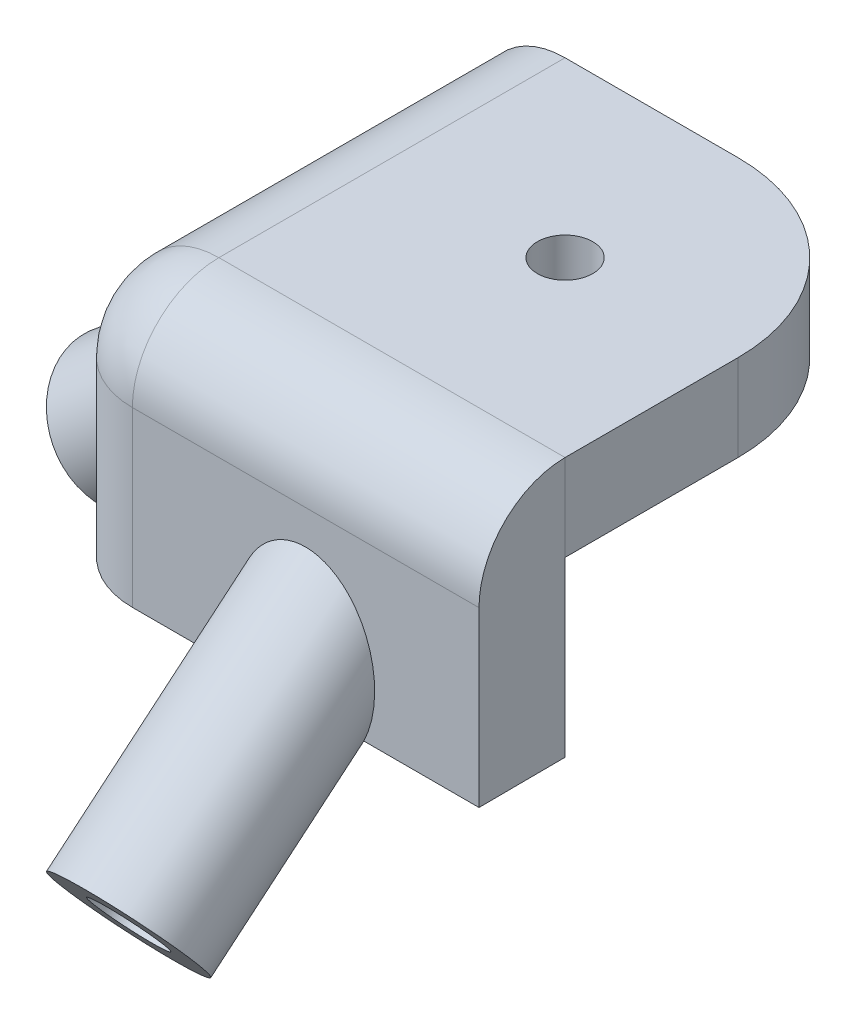
SolidWorks part; units mm, degrees
ref_plane "前基準面" through (0, 0, 0) normal (0, 0, 1) x (1, 0, 0)
ref_plane "上基準面" through (0, 0, 0) normal (0, 1, 0) x (1, 0, 0)
ref_plane "右基準面" through (0, 0, 0) normal (1, 0, 0) x (0, 0, -1)
sketch "草圖1" plane through (0, 0, 0) normal (0, 1, 0) x (1, 0, 0)
  line L1 (-10, -10) -> (10, -10)
  line L2 (-10, -10) -> (-10, 10)
  line L3 (-10, 10) -> (10, 10)
  line L4 (10, -10) -> (10, 10)
  line L5 (-10, -10) -> (10, 10) construction
  line L6 (-10, 10) -> (10, -10) construction
  point P0 (0, 0)
  dimension "D1" = 20
  dimension "D2" = 20
extrude "填料-伸長1" add sketch "草圖1" along normal blind 8
ref_plane "平面1" through (0, -1.6186, 1.929) normal (0, -0.6428, 0.766) x (1, 0, 0)
sketch "草圖2" plane through (0, -1.6186, 1.929) normal (0, -0.6428, 0.766) x (1, 0, 0)
  line L0 (-10, 6.4279) -> (10, 6.4279) construction
  line L1 (-10, 6.4279) -> (10, 6.4279) construction
  circle A0 centre (0, 6.4279) radius 4
  dimension "D1" = 8
extrude "填料-伸長2" add sketch "草圖2" along normal blind 25
ref_plane "平面2" through (-1.929, -1.6186, 0) normal (-0.766, -0.6428, 0) x (0, 0, 1)
sketch "草圖3" plane through (-1.929, -1.6186, 0) normal (-0.766, -0.6428, 0) x (0, 0, 1)
  line L0 (-10, 6.4279) -> (10, 6.4279) construction
  line L1 (-10, 6.4279) -> (10, 6.4279) construction
  circle A0 centre (0, 6.4279) radius 4
  dimension "D1" = 8
extrude "填料-伸長3" add sketch "草圖3" along normal blind 25
sketch "草圖4" plane through (0, 8, 0) normal (0, 1, 0) x (1, 0, 0)
  line L0 (0, 10) -> (10, 10)
  line L1 (10, 10) -> (10, 0)
  circle A0 centre (0, 0) radius 1.6
  arc A1 (10, 0) -> (0, 10) centre (0, 0) ccw
  dimension "D1" = 3.2
  dimension "D2" = 20
extrude "除料-伸長1" cut sketch "草圖4" against normal through all
sketch "草圖5" plane through (0, 0, 0) normal (0, -1, 0) x (1, 0, 0)
  line L0 (0, -10) -> (-10, -10) construction
  line L1 (10, 10) -> (10, 0) construction
  line L2 (0, -10) -> (-10, -10)
  line L3 (10, 10) -> (10, 0)
  line L4 (10, 10) -> (-10, 10)
  line L5 (-10, 10) -> (-10, -10)
  arc A0 (0, -10) -> (10, 0) centre (0, 0) ccw construction
  arc A1 (0, -10) -> (10, 0) centre (0, 0) ccw
sketch "草圖7" plane through (0, 0, 0) normal (0, -1, 0) x (1, 0, 0)
  line L0 (0, -10) -> (-10, -10) construction
  line L3 (4.3431, 4.3431) -> (-4.3431, 4.3431)
  line L4 (-4.3431, -4.3431) -> (-4.3431, 4.3431)
  line L7 (10, 10) -> (10, 0) construction
  line L8 (0, -10) -> (-4.3431, -10)
  line L9 (10, 4.3431) -> (10, 0)
  line L10 (4.3431, 4.3431) -> (10, 4.3431)
  line L11 (-4.3431, -4.3431) -> (-4.3431, -10)
  arc A0 (0, -10) -> (10, 0) centre (0, 0) ccw construction
  arc A1 (0, -10) -> (10, 0) centre (0, 0) ccw
  point P1 (0, 0)
sketch "草圖9" plane through (0, 8, 0) normal (0, 1, 0) x (1, 0, 0)
  line L0 (-10, 10) -> (-15, 10)
  line L1 (-15, 10) -> (-15, -15)
  line L2 (-15, -15) -> (10.0286, -15)
  line L3 (10.0286, -15) -> (10, -10)
  line L4 (10, -10) -> (-10, -10)
  line L5 (-10, -10) -> (-10, 10)
  dimension "D1" = 5
  dimension "D2" = 5
extrude "填料-伸長4" add sketch "草圖9" against normal blind 15
sketch "草圖10" plane through (0, -7, 0) normal (0, -1, 0) x (1, 0, 0)
  line L0 (10, 0) -> (10, 10)
  line L1 (10, 10) -> (-10, 10)
  line L2 (-10, 10) -> (-10, -10)
  line L3 (-10, -10) -> (0, -10)
  arc A0 (0, -10) -> (10, 0) centre (0, 0) ccw construction
  arc A1 (0, -10) -> (10, 0) centre (0, 0) ccw
extrude "除料-伸長5" cut sketch "草圖10" against normal blind 10
sketch "草圖11" plane through (-21.0801, -17.6883, 0) normal (-0.766, -0.6428, 0) x (0, 0, 1)
  circle A0 centre (0, 6.4279) radius 4 construction
  circle A1 centre (0, 6.4279) radius 4 construction
  circle A2 centre (0, 6.4279) radius 2.05
  dimension "D1" = 4.1
extrude "除料-伸長6" cut sketch "草圖11" against normal blind 10
sketch "草圖12" plane through (0, -17.6883, 21.0801) normal (0, -0.6428, 0.766) x (1, 0, 0)
  circle A0 centre (0, 6.4279) radius 4 construction
  circle A1 centre (0, 6.4279) radius 4 construction
  circle A2 centre (0, 6.4279) radius 2.05
  dimension "D1" = 4.1
extrude "除料-伸長7" cut sketch "草圖12" against normal blind 10
fillet "圓角3" radius 5 3 edges at (-2.4857, 8, 15) (-15, 8, 2.5) (-15, 0.5, 15)
